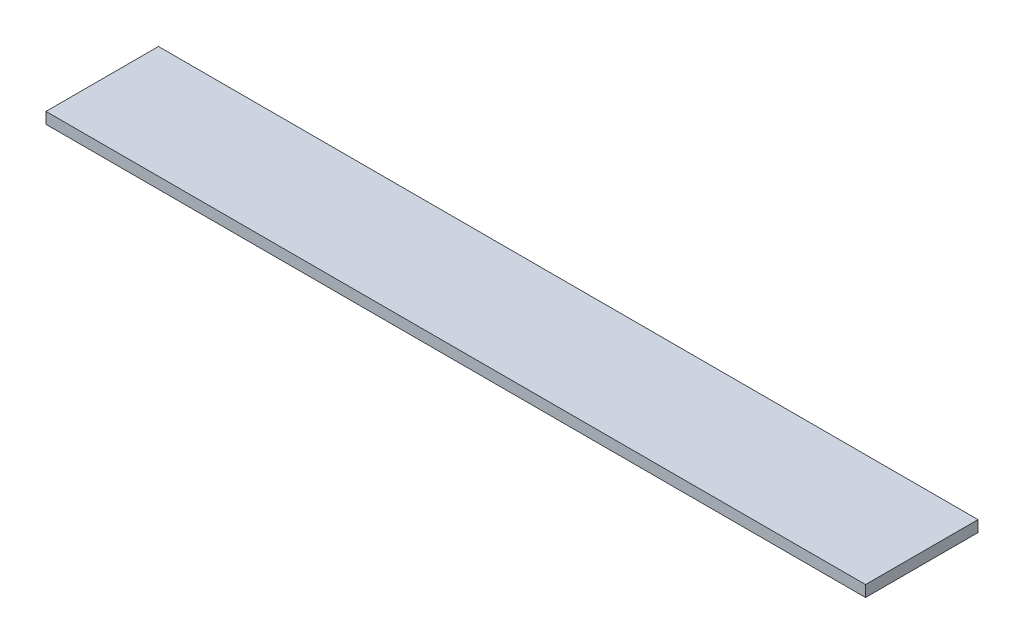
SolidWorks part; units mm, degrees
ref_plane "Front Plane" through (0, 0, 0) normal (0, 0, 1) x (1, 0, 0)
ref_plane "Top Plane" through (0, 0, 0) normal (0, 1, 0) x (1, 0, 0)
ref_plane "Right Plane" through (0, 0, 0) normal (1, 0, 0) x (0, 0, -1)
sketch "Sketch1" plane through (0, 0, 0) normal (0, 1, 0) x (1, 0, 0)
  line L1 (72.875, -10) -> (-72.875, -10)
  line L2 (72.875, -10) -> (72.875, 10)
  line L3 (72.875, 10) -> (-72.875, 10)
  line L4 (-72.875, -10) -> (-72.875, 10)
  line L5 (72.875, -10) -> (-72.875, 10) construction
  line L6 (72.875, 10) -> (-72.875, -10) construction
  point P0 (0, 0)
  dimension "D1" = 145.75
  dimension "D2" = 20
extrude "Boss-Extrude1" add sketch "Sketch1" along normal blind 2
